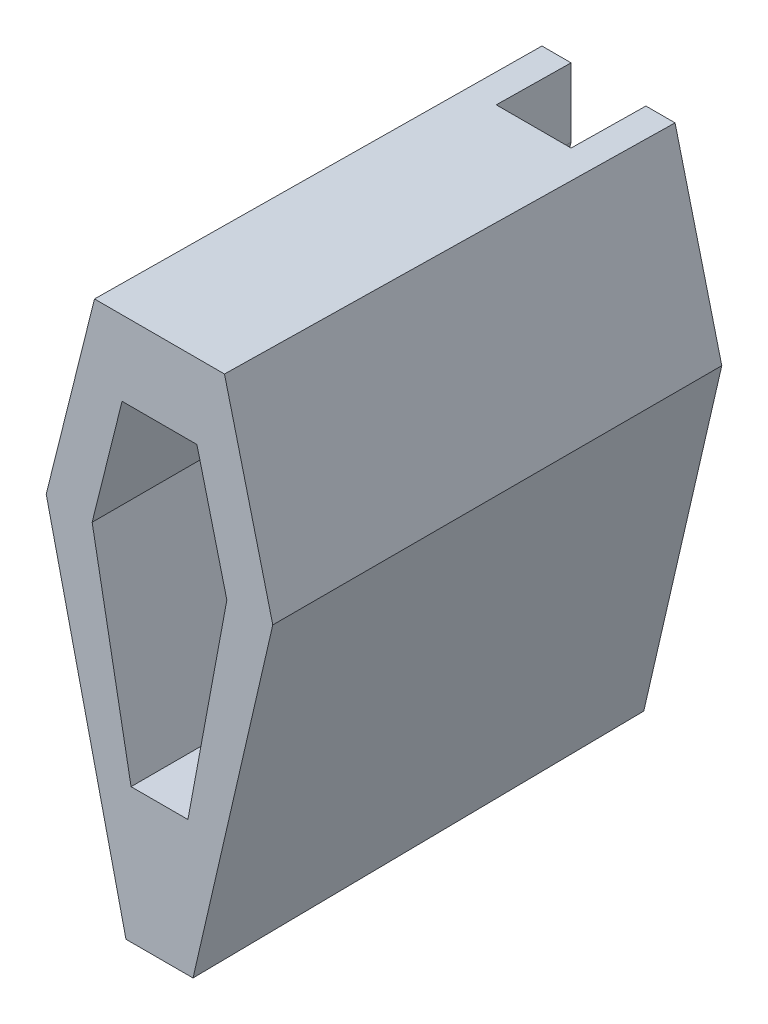
SolidWorks part; units mm, degrees
ref_plane "정면" through (0, 0, 0) normal (0, 0, 1) x (1, 0, 0)
ref_plane "윗면" through (0, 0, 0) normal (0, 1, 0) x (1, 0, 0)
ref_plane "우측면" through (0, 0, 0) normal (1, 0, 0) x (0, 0, -1)
sketch "스케치1" plane through (0, 0, 0) normal (0, 0, 1) x (1, 0, 0)
  line L0 (0, 9.1207) -> (0, -19.4097) construction
  line L1 (-10.4036, 0) -> (8.1695, 0) construction
  line L2 (2.5, 6.806) -> (-2.5, 6.806)
  line L3 (-2.5, 6.806) -> (-4.5, -1.194)
  line L4 (-4.5, -1.194) -> (-1.9, -15.194)
  line L5 (-1.9, -15.194) -> (1.9, -15.194)
  line L6 (4.5, -1.194) -> (1.9, -15.194)
  line L7 (2.5, 6.806) -> (4.5, -1.194)
  line L8 (3.2808, 7.806) -> (-3.2808, 7.806)
  line L9 (-3.2808, 7.806) -> (-5.5229, -1.1626)
  line L10 (-5.5229, -1.1626) -> (-2.7314, -16.194)
  line L11 (-2.7314, -16.194) -> (2.7314, -16.194)
  line L12 (5.5229, -1.1626) -> (2.7314, -16.194)
  line L13 (3.2808, 7.806) -> (5.5229, -1.1626)
  point P11 (0, -15.194)
  point P13 (0, 6.806)
  dimension "D1" = 9
  dimension "D2" = 5
  dimension "D3" = 3.8
  dimension "D4" = 14
  dimension "D5" = 22
  dimension "D6" = 1
ref_plane "평면1" through (0, 0, 30) normal (0, 0, 1) x (1, 0, 0)
sketch "스케치2" plane through (0, 0, 30) normal (0, 0, 1) x (1, 0, 0)
  line L6 (-2.5, 6.806) -> (-4.5, -1.194)
  line L7 (2.5, 6.806) -> (-2.5, 6.806)
  line L8 (2.5, 6.806) -> (4.5, -1.194)
  line L9 (4.5, -1.194) -> (1.9, -15.194)
  line L10 (-4.5, -1.194) -> (-1.9, -15.194)
  line L11 (-1.9, -15.194) -> (1.9, -15.194)
  line L12 (-3.2808, 7.806) -> (-5.5229, -1.1626)
  line L13 (-5.5229, -1.1626) -> (-2.7314, -16.194)
  line L14 (-2.7314, -16.194) -> (2.7314, -16.194)
  line L15 (5.5229, -1.1626) -> (2.7314, -16.194)
  line L16 (3.2808, 7.806) -> (5.5229, -1.1626)
  line L17 (3.2808, 7.806) -> (-3.2808, 7.806)
  dimension "D1" = 1
sketch "스케치3" plane through (0, 0, 0) normal (0, 0, 1) x (1, 0, 0)
  line L2 (-4.4464, 11.3895) -> (4.4464, 11.3895)
  line L10 (0, 14.306) -> (0, -22.694) construction
  line L14 (-2.3556, -23.694) -> (-7.5688, -1.0998)
  line L16 (7.5688, -1.0998) -> (2.3556, -23.694)
  line L17 (7.5688, -1.0998) -> (4.4464, 11.3895)
  line L19 (-7.5688, -1.0998) -> (-4.4464, 11.3895)
  line L21 (-2.3556, -23.694) -> (2.3556, -23.694)
  point P3 (-1.6558, 14.306)
  point P7 (1.5242, -22.694)
  point P8 (1.6558, 14.306)
  point P11 (3.2173, 16.306)
  point P16 (-1.5242, -22.694)
  point P17 (-3.2173, 16.306)
sketch "스케치4" plane through (0, 0, 30) normal (0, 0, 1) x (1, 0, 0)
  line L0 (-4.3423, 11.806) -> (4.3423, 11.806)
  line L7 (4.3423, 11.806) -> (7.5688, -1.0998)
  line L9 (7.5688, -1.0998) -> (2.2403, -24.194)
  line L10 (7.5688, -1.0998) -> (2.3556, -23.694) construction
  line L14 (0, 15.806) -> (0, -24.194) construction
  line L19 (2.2403, -24.194) -> (-2.2403, -24.194)
  line L20 (-4.3423, 11.806) -> (-7.5688, -1.0998)
  line L21 (-7.5688, -1.0998) -> (-2.2403, -24.194)
  line L22 (-2.3556, -23.694) -> (-7.5688, -1.0998) construction
loft "로프트1" add profiles "스케치3", "스케치4"
extrude "컷-돌출1" cut sketch "스케치1" along normal through all contours L3 L4 L5 L6 L7 L2
sketch "스케치5" plane through (0, 0, 0) normal (0, 0, -1) x (-1, 0, 0)
  line L0 (-2.5, 6.806) -> (-2.5, 13.306)
  line L2 (2.5, 6.806) -> (2.5, 13.306)
  line L3 (2.5, 13.306) -> (-2.5, 13.306)
  line L4 (-2.5, 6.806) -> (2.5, 6.806)
extrude "컷-돌출2" cut sketch "스케치5" against normal blind 5
